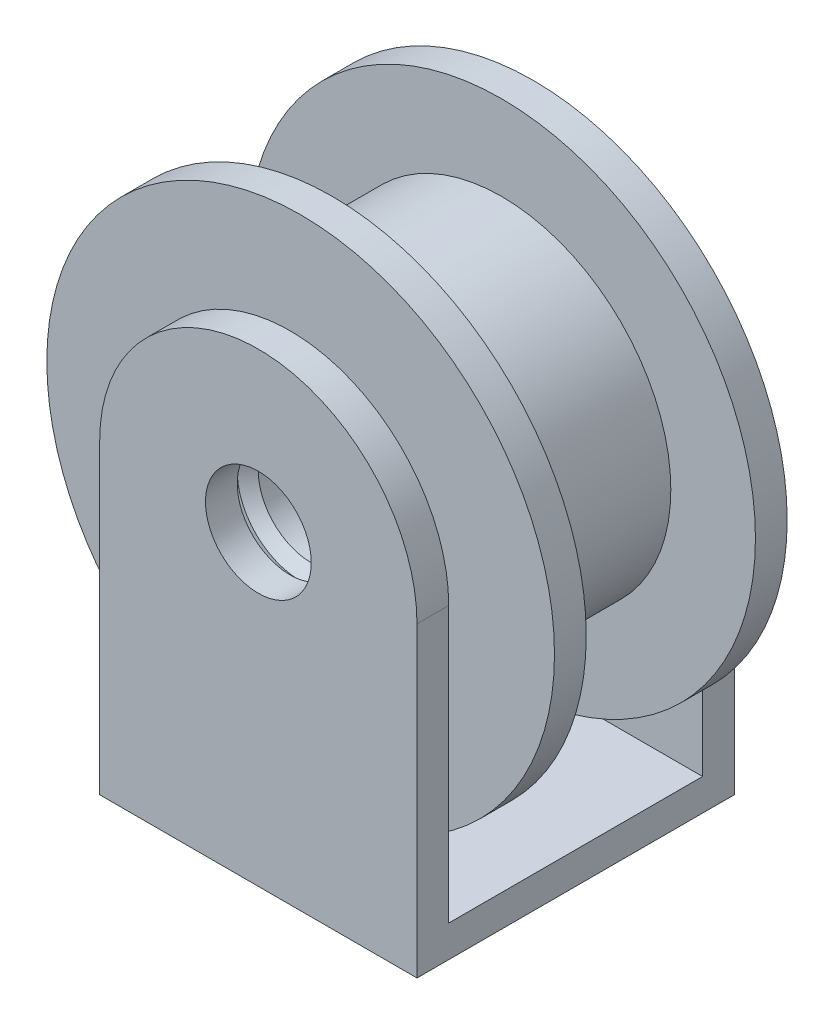
SolidWorks part; units mm, degrees
ref_plane "前视基准面" through (0, 0, 0) normal (0, 0, 1) x (1, 0, 0)
ref_plane "上视基准面" through (0, 0, 0) normal (0, 1, 0) x (1, 0, 0)
ref_plane "右视基准面" through (0, 0, 0) normal (1, 0, 0) x (0, 0, -1)
sketch "草图3" plane through (0, 0, 0) normal (0, 0, 1) x (1, 0, 0)
  circle A0 centre (0, 0) radius 16
  dimension "D1" = 32
extrude "凸台-拉伸3" add sketch "草图3" along normal blind 16
sketch "草图4" plane through (0, 0, 0) normal (0, 0, -1) x (-1, 0, 0)
  circle A0 centre (0, 0) radius 24
  dimension "D1" = 48
extrude "凸台-拉伸4" add sketch "草图4" along normal blind 3
sketch "草图5" plane through (0, 0, 16) normal (0, 0, 1) x (1, 0, 0)
  circle A0 centre (0, 0) radius 24
  dimension "D1" = 48
extrude "凸台-拉伸5" add sketch "草图5" along normal blind 3
sketch "草图6" plane through (0, 0, -3) normal (0, 0, -1) x (-1, 0, 0)
  circle A0 centre (0, 0) radius 5
  dimension "D1" = 10
extrude "切除-拉伸1" cut sketch "草图6" against normal up to surface (22 mm away) up to face at (24, 0, 19)
chamfer "倒角1" distance 1 angle 45 2 edges at (5, 0, 19) (-5, 0, -3)
ref_plane "基准面1" through (0, 0, -7) normal (0, 0, -1) x (-1, 0, 0)
sketch "草图8" plane through (0, 0, -7) normal (0, 0, -1) x (-1, 0, 0)
  line L0 (-15, 0) -> (-15, -29)
  line L1 (-15, -29) -> (15, -29)
  line L2 (15, -29) -> (15, 0)
  line L3 (0, 0) -> (0, 31.8504) construction
  arc A0 (15, 0) -> (-15, 0) centre (0, 0) ccw
  circle A1 centre (0, 0) radius 24 construction
  circle A2 centre (0, 0) radius 24 construction
  point P2 (-16.0261, -29)
  point P8 (0, 24)
  point P11 (15, -31.2084)
  point P13 (0, 24)
  point P14 (15, -31.48)
  point P15 (0, 24)
  point P16 (15, -29)
  point P17 (15, -38.7443)
  point P18 (0, 24)
  point P19 (0, 0)
  dimension "D1" = 30
  dimension "D2" = 29
extrude "凸台-拉伸6" add sketch "草图8" against normal blind 3 separate body
ref_plane "基准面2" through (0, 0, 8) normal (0, 0, 1) x (1, 0, 0)
mirror "镜向5" about plane through (0, 0, 8) normal (0, 0, 1) of bodies 112
sketch "草图9" plane through (0, 0, -4) normal (0, 0, 1) x (1, 0, 0)
  line L0 (-15, -29) -> (15, -29)
  line L1 (15, -29) -> (15, -26)
  line L2 (15, 0) -> (15, -29) construction
  line L3 (15, -26) -> (-15, -26)
  line L4 (-15, -29) -> (-15, 0) construction
  line L5 (-15, -26) -> (-15, -29)
  dimension "D1" = 3
extrude "凸台-拉伸7" add sketch "草图9" along normal up to next
sketch "草图10" plane through (0, 0, -7) normal (0, 0, -1) x (-1, 0, 0)
  circle A0 centre (0, 0) radius 5
  dimension "D1" = 10
extrude "切除-拉伸2" cut sketch "草图10" against normal up to surface (30 mm away) up to face at (0, -10.75, 23)
sketch "草图11" plane through (0, -29, 0) normal (0, -1, 0) x (1, 0, 0)
  line L0 (0, 0) -> (0, 33.7504) construction
  line L1 (-15, 8) -> (15, 8) construction
  line L2 (-15, 23) -> (-15, -7) construction
  line L3 (15, 23) -> (15, -7) construction
  circle A0 centre (0, 8) radius 5
  dimension "D1" = 10
extrude "切除-拉伸3" cut sketch "草图11" against normal up to next (3 mm away)
